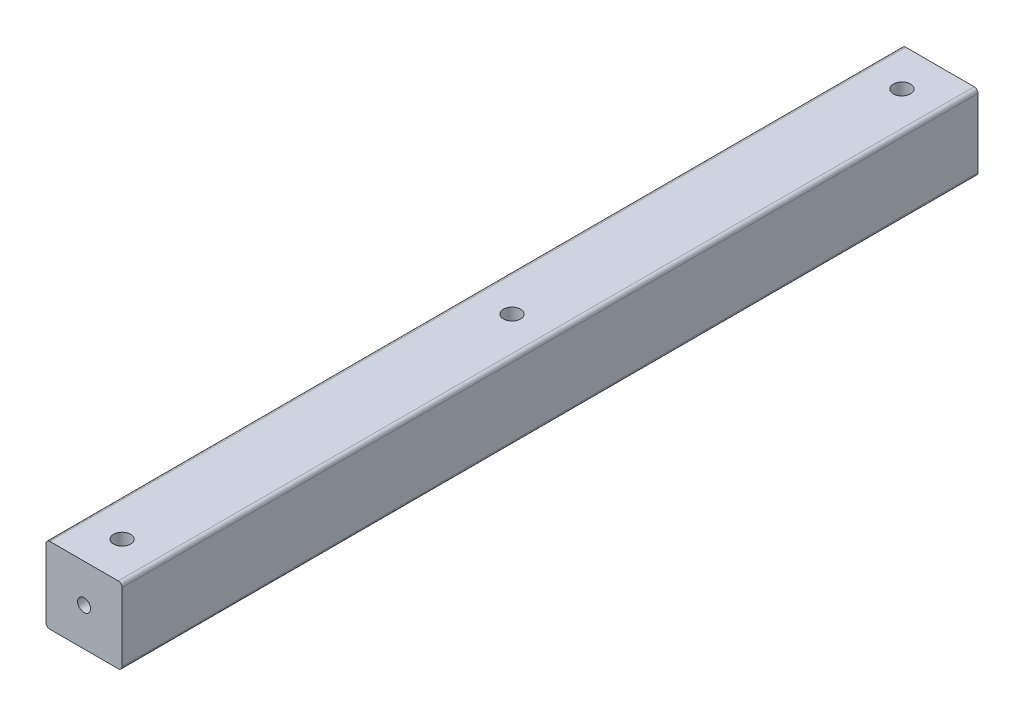
SolidWorks part; units mm, degrees
ref_plane "Front Plane" through (0, 0, 0) normal (0, 0, 1) x (1, 0, 0)
ref_plane "Top Plane" through (0, 0, 0) normal (0, 1, 0) x (1, 0, 0)
ref_plane "Right Plane" through (0, 0, 0) normal (1, 0, 0) x (0, 0, -1)
sketch "Sketch1" plane through (0, 0, 0) normal (0, 0, 1) x (1, 0, 0)
  line L1 (-20, -20) -> (20, -20)
  line L2 (-20, -20) -> (-20, 20)
  line L3 (-20, 20) -> (20, 20)
  line L4 (20, -20) -> (20, 20)
  line L5 (-20, -20) -> (20, 20) construction
  line L6 (-20, 20) -> (20, -20) construction
  circle A0 centre (0, 0) radius 2.5
  point P0 (0, 0)
  dimension "D3" = 5
  dimension "D1" = 40
  dimension "D2" = 40
extrude "Boss-Extrude1" add sketch "Sketch1" along normal mid plane 450
fillet "Fillet1" radius 2 4 edges at (20, -20, 0) (-20, -20, 0) (-20, 20, 0) (20, 20, 0)
sketch "Sketch2" plane through (0, 20, 0) normal (0, 1, 0) x (1, 0, 0)
  line L0 (0, 958.3172) -> (0, -945.7078) construction
  line L2 (18, 225) -> (-18, 225) construction
  line L3 (18, -225) -> (-18, -225) construction
  point P3 (0, -375)
  point P4 (0, 375)
  dimension "D1" = 600
  dimension "D2" = 600
hole_wizard "Ø4.5 (4.5) Diameter Hole1" positions "Sketch3" profile "Sketch4" hole size "Ø4.5" standard "ISO"
sketch "Sketch3" plane through (0, 20, 0) normal (0, 1, 0) x (1, 0, 0)
  point P0 (0, -300)
  point P3 (0, 300)
sketch "Sketch4" plane through (0, 20, 300) normal (1, 0, 0) x (0, 0, 1)
  line L0 (0, 0) -> (0, 40)
  line L1 (0, 40) -> (2.25, 40)
  line L2 (2.25, 40) -> (2.25, 0)
  line L5 (2.25, 0) -> (0, 0)
  line L11 (0, -6.35) -> (0, 107.95) construction
  dimension "Thru Hole Dia." = 4.5
  dimension "Thru Hole Depth" = 40
sketch "Sketch5" plane through (0, -20, 0) normal (0, -1, 0) x (1, 0, 0)
  line L0 (0, 225) -> (0, -1000.0028) construction
  line L1 (-18, 225) -> (18, 225) construction
  line L2 (-18, -225) -> (18, -225) construction
  point P4 (0, 205)
  point P5 (0, 500)
  point P6 (0, 0)
  point P7 (0, -500)
  point P8 (0, -205)
  dimension "D1" = 500
  dimension "D2" = 500
  dimension "D3" = 20
  dimension "D4" = 20
hole_wizard "CBORE for M8 Hex Socket Head Cap Screw1" positions "Sketch6" profile "Sketch7" counterbore size "M8" standard "ISO" end condition through all
sketch "Sketch6" plane through (0, -20, 0) normal (0, -1, 0) x (-1, 0, 0)
  point P0 (0, 500)
  point P3 (0, 0)
  point P6 (0, -500)
  point P9 (0, 205)
  point P12 (0, -205)
sketch "Sketch7" plane through (0, -20, -500) normal (1, 0, 0) x (0, 0, -1)
  line L0 (0, 0) -> (0, 40)
  line L1 (0, 40) -> (4.5, 40)
  line L3 (4.5, 40) -> (4.5, 8.6)
  line L4 (4.5, 8.6) -> (7.5, 8.6)
  line L5 (7.5, 8.6) -> (7.5, 0)
  line L7 (7.5, 0) -> (0, 0)
  line L11 (0, -6.35) -> (0, 107.95) construction
  dimension "Thru Hole Dia." = 9
  dimension "Thru Hole Depth" = 40
  dimension "C'Bore Dia." = 15
  dimension "C'Bore Depth" = 8.6
hole_wizard "M8x1.25 Tapped Hole1" positions "Sketch8" profile "Sketch9" tap size "M8x1.25" standard "ANSI Metric"
sketch "Sketch8" plane through (0, 0, 225) normal (0, 0, 1) x (1, 0, 0)
  point P0 (0, 0)
sketch "Sketch9" plane through (0, 0, 225) normal (1, 0, 0) x (0, -1, 0)
  line L0 (0, 0) -> (0, 29.7929)
  line L1 (0, 29.7929) -> (3.4, 27.75)
  line L2 (3.4, 27.75) -> (3.4, 0)
  line L5 (3.4, 0) -> (0, 0)
  line L10 (0, 29.7929) -> (-3.4, 27.75) construction
  line L11 (0, -6.35) -> (0, 107.95) construction
  dimension "Tap Drill Dia." = 6.8
  dimension "Tap Drill Depth" = 27.75
  dimension "Drill Angle" = 118
cosmetic thread "Hole Thread1" parameters "D1"=24, "D2"=8
mirror "Mirror1" about plane through (0, 0, 0) normal (0, 0, 1) of "M8x1.25 Tapped Hole1"
cosmetic thread "Hole Thread2" parameters "D1"=24, "D2"=8
